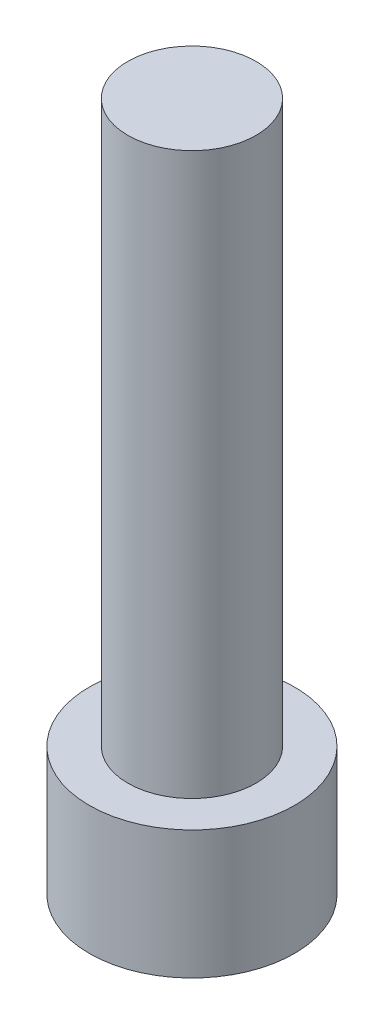
SolidWorks part; units mm, degrees
ref_plane "Спереди" through (0, 0, 0) normal (0, 0, 1) x (1, 0, 0)
ref_plane "Сверху" through (0, 0, 0) normal (0, 1, 0) x (1, 0, 0)
ref_plane "Справа" through (0, 0, 0) normal (1, 0, 0) x (0, 0, -1)
sketch "Эскиз2" plane through (0, 0, 0) normal (0, 1, 0) x (1, 0, 0)
  circle A0 centre (0, 0) radius 6.4
extrude "Вытянуть1" add sketch "Эскиз2" along normal blind 8
sketch "Эскиз3" plane through (0, 0, 0) normal (0, -1, 0) x (1, 0, 0)
  line L1 (-1.6433, -4.0062) -> (2.6478, -3.4262)
  line L2 (2.6478, -3.4262) -> (4.2911, 0.58)
  line L3 (4.2911, 0.58) -> (1.6433, 4.0062)
  line L4 (1.6433, 4.0062) -> (-2.6478, 3.4262)
  line L5 (-2.6478, 3.4262) -> (-4.2911, -0.58)
  line L6 (-4.2911, -0.58) -> (-1.6433, -4.0062)
  circle A0 centre (0, 0) radius 3.75 construction
  dimension "D1" = 7.5
extrude "Вытянуть2" cut sketch "Эскиз3" against normal blind 6
sketch "Эскиз4" plane through (0, 8, 0) normal (0, 1, 0) x (-1, 0, 0)
  circle A0 centre (0, 0) radius 4
extrude "Вытянуть3" add sketch "Эскиз4" along normal blind 35
